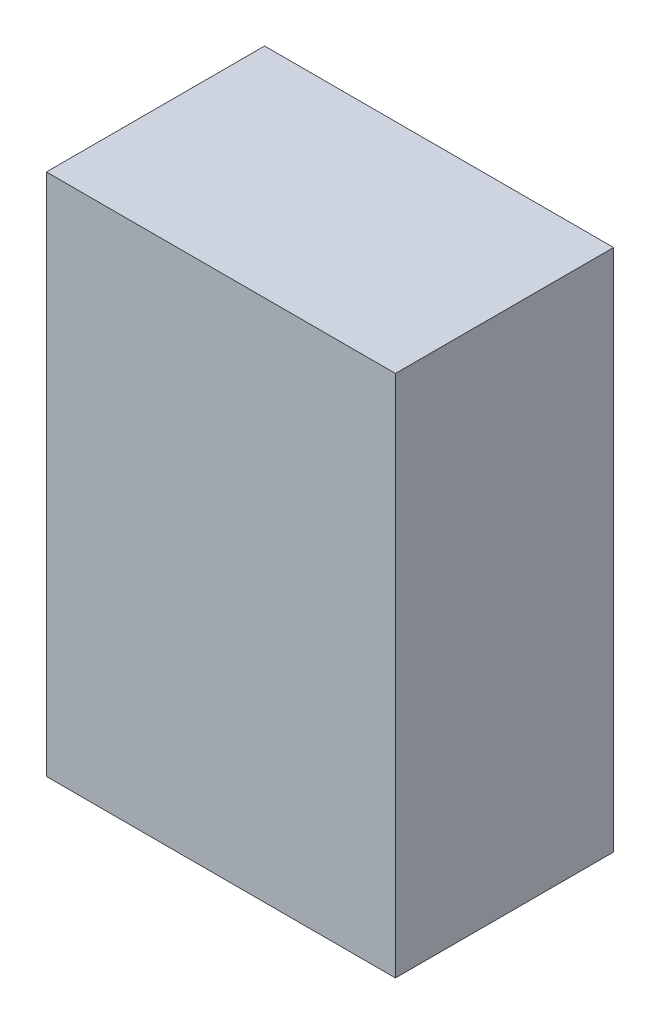
SolidWorks part; units mm, degrees
ref_plane "前视基准面" through (0, 0, 0) normal (0, 0, 1) x (1, 0, 0)
ref_plane "上视基准面" through (0, 0, 0) normal (0, 1, 0) x (1, 0, 0)
ref_plane "右视基准面" through (0, 0, 0) normal (1, 0, 0) x (0, 0, -1)
other "Configuration Table"
sketch "草图1" plane through (0, 0, 0) normal (0, 1, 0) x (1, 0, 0)
  line L1 (-40, -25) -> (40, -25)
  line L2 (-40, -25) -> (-40, 25)
  line L3 (-40, 25) -> (40, 25)
  line L4 (40, -25) -> (40, 25)
  line L5 (-40, -25) -> (40, 25) construction
  line L6 (-40, 25) -> (40, -25) construction
  point P0 (0, 0)
  dimension "D1" = 80
  dimension "D2" = 50
extrude "凸台-拉伸1" add sketch "草图1" along normal blind 120
